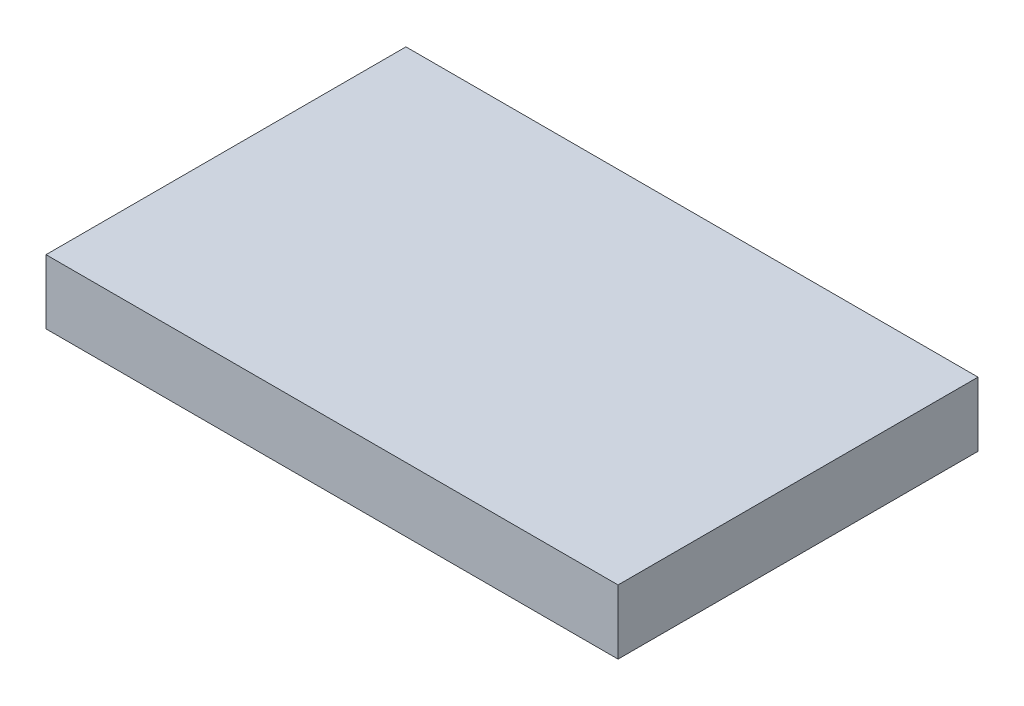
SolidWorks part; units mm, degrees
ref_plane "Front Plane" through (0, 0, 0) normal (0, 0, 1) x (1, 0, 0)
ref_plane "Top Plane" through (0, 0, 0) normal (0, 1, 0) x (1, 0, 0)
ref_plane "Right Plane" through (0, 0, 0) normal (1, 0, 0) x (0, 0, -1)
sketch "Sketch1" plane through (0, 0, 0) normal (0, 1, 0) x (1, 0, 0)
  line L1 (-44.5, -28) -> (44.5, -28)
  line L2 (-44.5, -28) -> (-44.5, 28)
  line L3 (-44.5, 28) -> (44.5, 28)
  line L4 (44.5, -28) -> (44.5, 28)
  line L5 (-44.5, -28) -> (44.5, 28) construction
  line L6 (-44.5, 28) -> (44.5, -28) construction
  point P0 (0, 0)
  dimension "D1" = 56
  dimension "D2" = 89
extrude "Boss-Extrude1" add sketch "Sketch1" along normal mid plane 10
